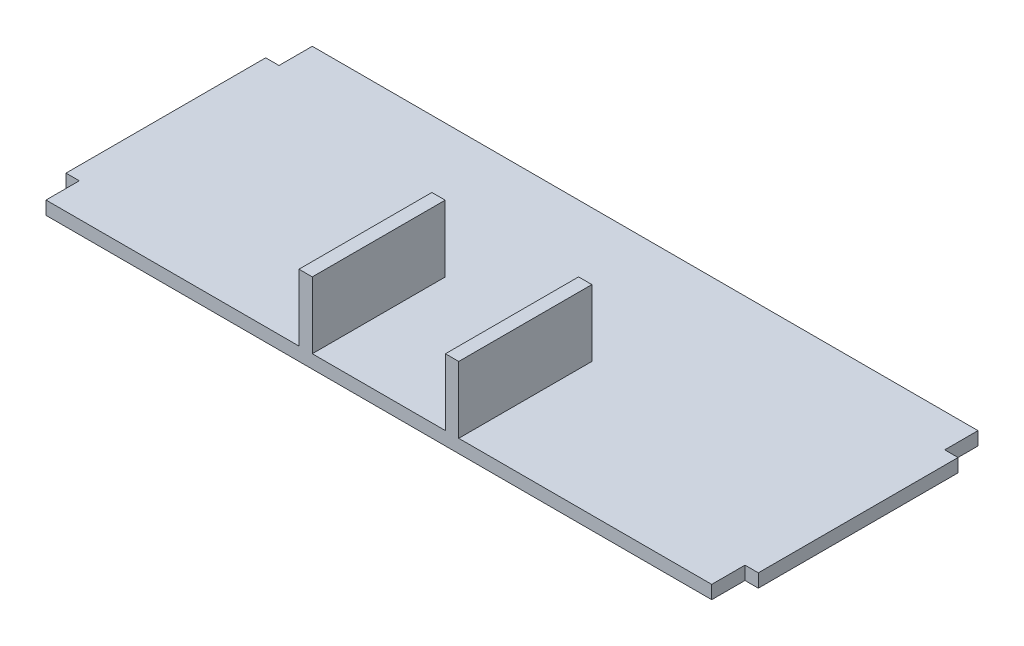
SolidWorks part; units mm, degrees
ref_plane "前视基准面" through (0, 0, 0) normal (0, 0, 1) x (1, 0, 0)
ref_plane "上视基准面" through (0, 0, 0) normal (0, 1, 0) x (1, 0, 0)
ref_plane "右视基准面" through (0, 0, 0) normal (1, 0, 0) x (0, 0, -1)
sketch "草图1" plane through (0, 0, 0) normal (0, 1, 0) x (1, 0, 0)
  line L0 (0, 40) -> (0, 0)
  line L1 (0, 40) -> (100, 40)
  line L2 (0, 0) -> (100, 0)
  line L3 (100, 40) -> (100, 0)
  line L4 (-2, 35) -> (-2, 5)
  line L5 (-2, 35) -> (0, 35)
  line L6 (-2, 5) -> (0, 5)
  line L7 (0, 35) -> (0, 5)
  line L8 (100, 35) -> (102, 35)
  line L9 (100, 35) -> (100, 5)
  line L10 (102, 35) -> (102, 5)
  line L11 (100, 5) -> (102, 5)
  line L12 (38, 0) -> (38, 20)
  line L13 (38, 0) -> (40, 0)
  line L14 (38, 20) -> (40, 20)
  line L15 (40, 0) -> (40, 20)
  line L16 (60, 0) -> (60, 20)
  line L17 (60, 0) -> (62, 0)
  line L18 (60, 20) -> (62, 20)
  line L19 (62, 0) -> (62, 20)
  point P0 (0, 40)
  point P1 (0, 0)
  point P2 (0, 0)
  point P3 (100, 40)
  point P4 (100, 0)
  point P5 (0, 5)
  point P6 (0, 35)
  point P7 (100, 35)
  point P8 (100, 5)
  point P9 (-2, 35)
  point P10 (-2, 5)
  point P11 (102, 35)
  point P12 (102, 5)
extrude "凸台-拉伸3" add sketch "草图1" along normal blind 2 contours L19 L2 L3 L1 L0 L12 L14 L15 L16 L18 | L4 L6 L0 L5 | L3 L11 L10 L8
sketch "草图3" plane through (0, 0, 0) normal (0, 1, 0) x (1, 0, 0)
  line L0 (38, 0) -> (40, 0)
  line L1 (38, 0) -> (38, 19.9636)
  line L2 (40, 0) -> (40, 19.9636)
  line L3 (38, 19.9636) -> (40, 19.9636)
  line L4 (60, 0) -> (62, 0)
  line L5 (60, 0) -> (60, 20)
  line L6 (62, 0) -> (62, 20)
  line L7 (60, 20) -> (62, 20)
extrude "凸台-拉伸4" add sketch "草图3" along normal blind 12 contours L3 L1 L0 L2 | L7 L5 L4 L6
